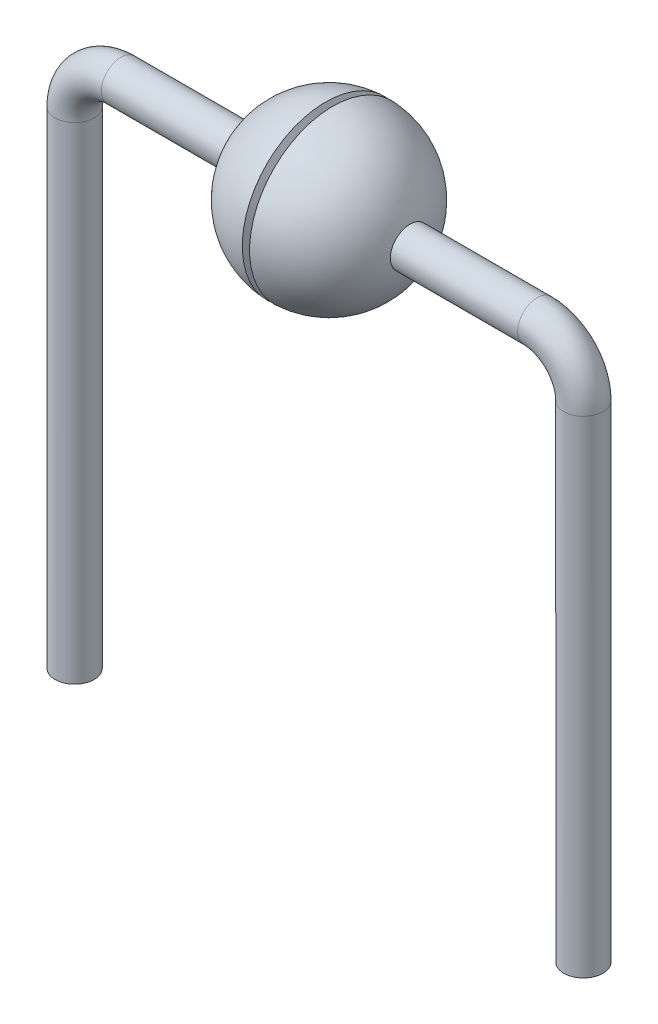
SolidWorks part; units mm, degrees
ref_plane "Спереди" through (0, 0, 0) normal (0, 0, 1) x (1, 0, 0)
ref_plane "Сверху" through (0, 0, 0) normal (0, 1, 0) x (1, 0, 0)
ref_plane "Справа" through (0, 0, 0) normal (1, 0, 0) x (0, 0, -1)
sketch "Эскиз1" plane through (0, 0, 0) normal (0, 1, 0) x (1, 0, 0)
  line L0 (-29.7512, 0) -> (31.712, 0) construction
  line L1 (-1.7496, 0.4231) -> (-1.7496, 0)
  line L2 (-1.7496, 0) -> (1.7496, 0)
  line L4 (1.7496, 0) -> (1.7496, 0.4231)
  line L5 (-0.0758, 1.7984) -> (0, 1.6459)
  line L6 (0, 1.6459) -> (0.081, 1.7982)
  line L7 (0, 1.6459) -> (0, -0.8803) construction
  arc A0 (0.081, 1.7982) -> (1.7496, 0.4231) centre (0, 0) cw
  arc A1 (-1.7496, 0.4231) -> (-0.0758, 1.7984) centre (0, 0) cw
revolve "Повернуть2" add sketch "Эскиз1" angle 360 about L0
sketch "Эскиз2" plane through (0, 0, 0) normal (0, 0, 1) x (1, 0, 0)
  line L0 (0, 0) -> (-4.5, 0)
  line L1 (-5.5, -1) -> (-5.5, -11.5149)
  arc A1 (-4.5, 0) -> (-5.5, -1) centre (-4.5, -1) ccw
  dimension "D2" = 5.5
sketch "Эскиз3" plane through (-1.7496, 0, 0) normal (-1, 0, 0) x (0, 0, 1)
  circle A0 centre (0, 0) radius 0.4231
sweep "По траектории1" add profiles "Эскиз3" path "Эскиз2"
mirror "Зеркальное отражение1" about plane through (0, 0, 0) normal (1, 0, 0) of "По траектории1"
